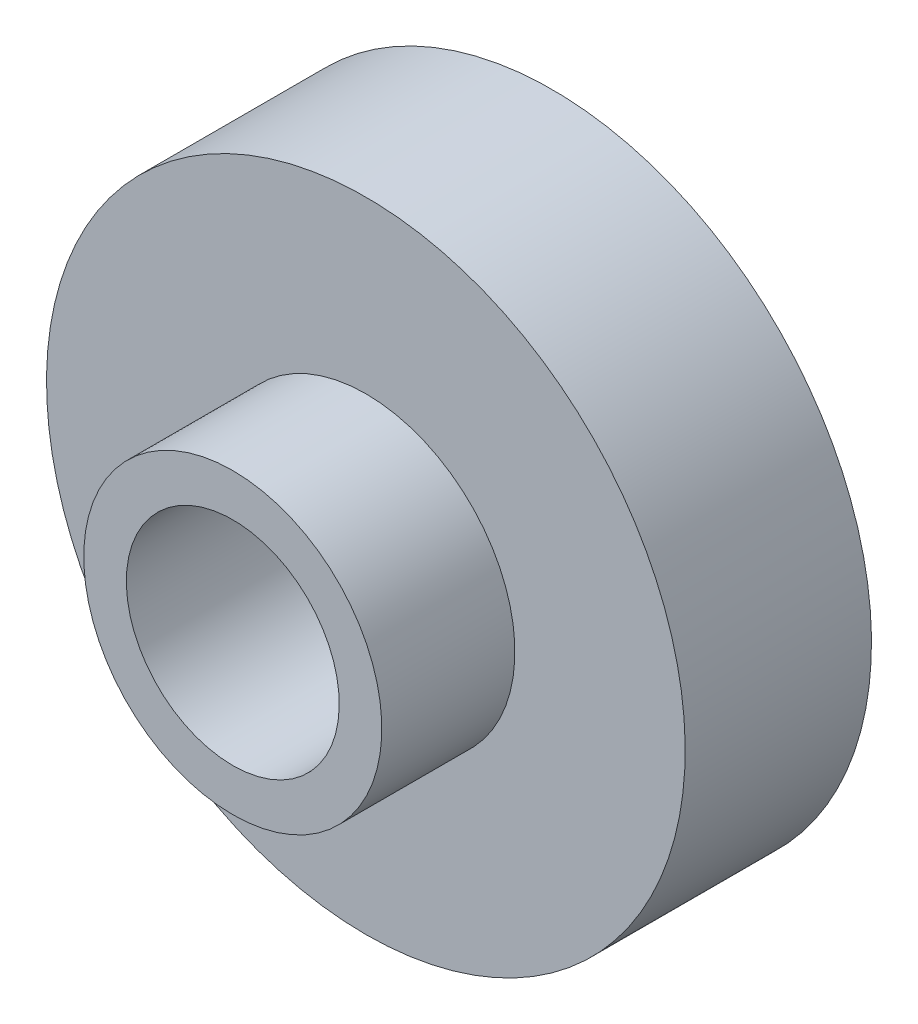
SolidWorks part; units mm, degrees
ref_plane "Front" through (0, 0, 0) normal (0, 0, 1) x (1, 0, 0)
ref_plane "Top" through (0, 0, 0) normal (0, 1, 0) x (1, 0, 0)
ref_plane "Right" through (0, 0, 0) normal (1, 0, 0) x (0, 0, -1)
sketch "Sketch1" plane through (0, 0, 0) normal (1, 0, 0) x (0, 0, -1)
  line L0 (-152.4, 0) -> (1225.6578, 0) construction
  line L1 (-152.4, 71.12) -> (-152.4, 50.8)
  line L5 (-66.04, 50.8) -> (-66.04, 63.5)
  line L6 (-66.04, 63.5) -> (-40.64, 63.5)
  line L7 (-40.64, 63.5) -> (-40.64, 101.6)
  line L8 (-40.64, 101.6) -> (-58.42, 101.6)
  line L9 (-58.42, 101.6) -> (-58.42, 114.3)
  line L10 (-58.42, 114.3) -> (0, 114.3)
  line L11 (0, 114.3) -> (0, 152.4)
  line L12 (0, 152.4) -> (-88.9, 152.4)
  line L13 (-88.9, 152.4) -> (-88.9, 71.12)
  line L14 (-88.9, 71.12) -> (-152.4, 71.12)
  line L15 (0, -448.738) -> (0, 1645.2936) construction
  line L16 (-152.4, 50.8) -> (-66.04, 50.8)
  dimension "D1" = 152.4
  dimension "D2" = 88.9
  dimension "D3" = 12.7
  dimension "D4" = 101.6
  dimension "D5" = 71.12
  dimension "D6" = 25.4
  dimension "D7" = 38.1
  dimension "D8" = 12.7
  dimension "D9" = 152.4
  dimension "D10" = 30.48
  dimension "D11" = 17.78
revolve "Revolve1" add sketch "Sketch1" angle 360 about L0
